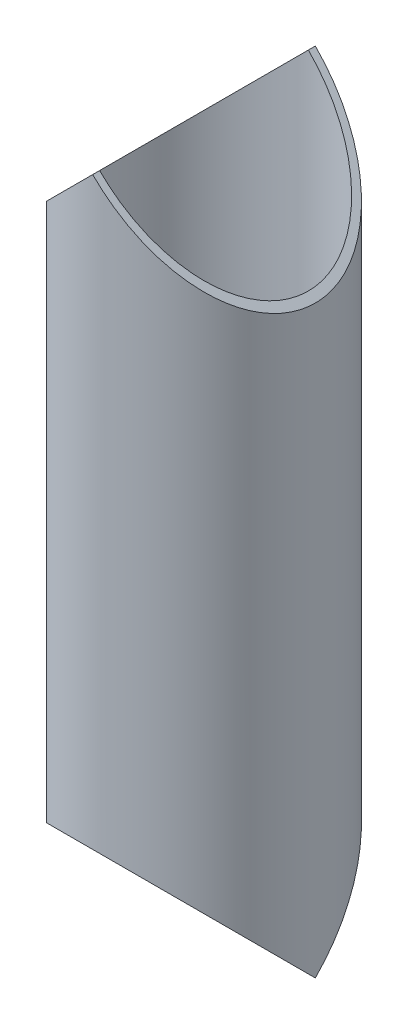
SolidWorks part; units mm, degrees
material "Acrylic (Medium-high impact)"
ref_plane "Front Plane" through (0, 0, 0) normal (0, 0, 1) x (1, 0, 0)
ref_plane "Top Plane" through (0, 0, 0) normal (0, 1, 0) x (1, 0, 0)
ref_plane "Right Plane" through (0, 0, 0) normal (1, 0, 0) x (0, 0, -1)
sketch "Sketch1" plane through (0, 0, 0) normal (0, 1, 0) x (1, 0, 0)
  circle A0 centre (0, 0) radius 25.4
  circle A1 centre (0, 0) radius 23.8125
  dimension "D1" = 50.8
  dimension "D2" = 1.5875
extrude "Boss-Extrude1" add sketch "Sketch1" along normal blind 158.75
sketch "Sketch2" plane through (0, 0, 0) normal (0, 0, 1) x (1, 0, 0)
  line L2 (-25.4, 158.75) -> (-25.4, 0) construction
  line L3 (25.4, 0) -> (25.4, 158.75) construction
  line L4 (25.4, 133.35) -> (25.4, 158.75)
  line L5 (25.4, 158.75) -> (-0.9601, 166.5405)
  line L6 (-0.9601, 166.5405) -> (-25.4, 158.75)
  line L7 (-25.4, 158.75) -> (-25.4, 133.35)
  line L9 (-25.4, 133.35) -> (0, 158.75)
  line L10 (0, 158.75) -> (25.4, 133.35)
  line L11 (25.4, 158.75) -> (-25.4, 158.75) construction
extrude "Cut-Extrude1" cut sketch "Sketch2" against normal through all and the other way through all
sketch "Sketch3" plane through (0, 0, 0) normal (1, 0, 0) x (0, 0, -1)
  line L0 (-25.4, 158.75) -> (-25.4, 0) construction
  line L1 (25.4, 0) -> (25.4, 158.75) construction
  line L2 (-25.4, 25.4) -> (-25.4, 0)
  line L3 (-25.4, 0) -> (0.0326, -12.1128)
  line L4 (0.0326, -12.1128) -> (25.4, 0)
  line L5 (25.4, 0) -> (25.4, 25.4)
  line L7 (25.4, 25.4) -> (0, 0)
  line L8 (-23.8125, 0) -> (23.8125, 0) construction
  line L9 (0, 0) -> (-25.4, 25.4)
extrude "Cut-Extrude2" cut sketch "Sketch3" against normal through all and the other way through all
